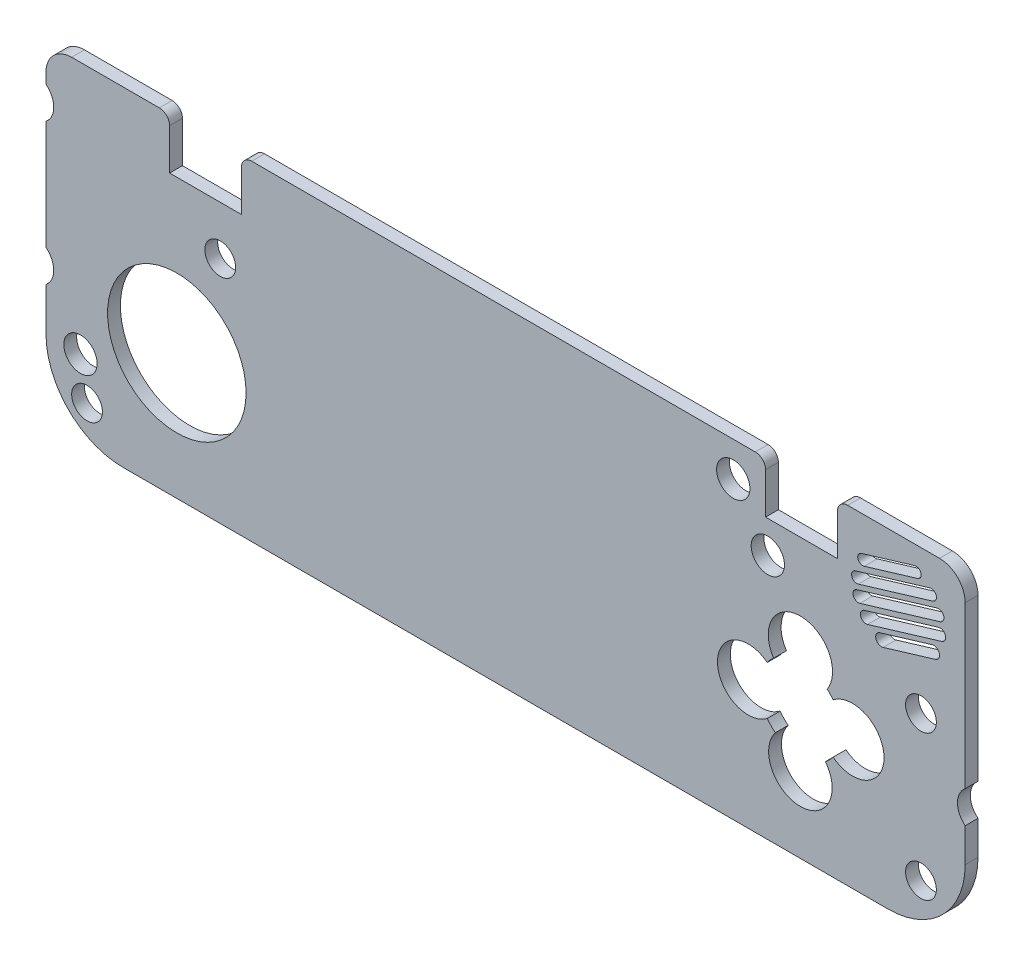
SolidWorks part; units mm, degrees
ref_plane "Plan de face" through (0, 0, 0) normal (0, 0, 1) x (1, 0, 0)
ref_plane "Plan de dessus" through (0, 0, 0) normal (0, 1, 0) x (1, 0, 0)
ref_plane "Plan de droite" through (0, 0, 0) normal (1, 0, 0) x (0, 0, -1)
sketch "Esquisse1" plane through (0, 0, 0) normal (0, 0, 1) x (1, 0, 0)
  line L1 (-89.2039, 33.3448) -> (79.9661, 33.3448)
  line L2 (-94.2039, 28.3448) -> (-94.2039, -15.8852)
  line L3 (-79.2039, -30.8852) -> (69.9661, -30.8852)
  line L4 (84.9661, 28.3448) -> (84.9661, -15.8852)
  arc A0 (-89.2039, 33.3448) -> (-94.2039, 28.3448) centre (-89.2039, 28.3448) ccw
  arc A1 (79.9661, 33.3448) -> (84.9661, 28.3448) centre (79.9661, 28.3448) cw
  arc A2 (69.9661, -30.8852) -> (84.9661, -15.8852) centre (69.9661, -15.8852) ccw
  arc A3 (-94.2039, -15.8852) -> (-79.2039, -30.8852) centre (-79.2039, -15.8852) ccw
  point P6 (-94.2039, 33.3448)
  point P9 (84.9661, 33.3448)
  point P12 (84.9661, -30.8852)
  dimension "D3" = 5
  dimension "D4" = 5
  dimension "D5" = 15
  dimension "D6" = 15
  dimension "D1" = 179.17
  dimension "D2" = 64.23
extrude "Boss.-Extru.1" add sketch "Esquisse1" along normal blind 2.5 contours L1 A1 L4 A2 L3 A3 L2 A0
sketch "12x12 Button" plane through (0, 0, 2.5) normal (0, 0, 1) x (1, 0, 0)
  line L0 (84.9661, 28.3448) -> (84.9661, -15.8852) construction
  line L1 (-79.2039, -30.8852) -> (69.9661, -30.8852) construction
  line L2 (52.8461, 3.7748) -> (52.8461, -15.9152)
  line L3 (42.6861, -5.7552) -> (63.0061, -5.7552)
  circle A0 centre (42.6861, -5.7552) radius 5.9988
  circle A1 centre (52.8461, 3.7748) radius 6.2634
  circle A2 centre (52.8461, -15.9152) radius 6.1927
  circle A3 centre (63.0061, -5.7552) radius 6.14
  arc A5 (46.3825, -1.0306) -> (47.6252, 0.3146) centre (52.8461, -5.7552) cw
  arc A6 (59.2204, -0.9212) -> (58.0635, 0.3093) centre (52.8461, -5.7552) ccw
  arc A7 (46.3874, -10.476) -> (47.9701, -12.0975) centre (52.8461, -5.7552) ccw
  arc A10 (57.722, -12.0975) -> (59.2204, -10.5893) centre (52.8461, -5.7552) ccw
  dimension "D1" = 21.96
  dimension "D2" = 32.12
  dimension "D3" = 42.28
  dimension "D4" = 32.12
  dimension "D5" = 14.97
  dimension "D6" = 34.66
  dimension "D7" = 25.13
  dimension "D8" = 25.13
extrude "Enlèv. mat.-Extru.14" cut sketch "12x12 Button" against normal blind 10
sketch "Joystick" plane through (0, 0, 2.5) normal (0, 0, 1) x (1, 0, 0)
  line L0 (-79.2039, -30.8852) -> (69.9661, -30.8852) construction
  line L1 (-94.2039, 28.3448) -> (-94.2039, -15.8852) construction
  circle A0 centre (-68.7039, -6.3252) radius 13.5
  dimension "D1" = 24.56
  dimension "D2" = 25.5
extrude "Enlèv. mat.-Extru.2" cut sketch "Joystick" against normal blind 2.5
sketch "Esquisse2" plane through (0, 0, 2.5) normal (0, 0, 1) x (1, 0, 0)
  line L0 (-89.2039, 33.3448) -> (79.9661, 33.3448) construction
  line L1 (46.0561, 33.3448) -> (60.0561, 33.3448)
  line L2 (46.0561, 33.3448) -> (46.0561, 23.3448)
  line L3 (46.0561, 23.3448) -> (60.0561, 23.3448)
  line L4 (60.0561, 33.3448) -> (60.0561, 23.3448)
  line L5 (84.9661, 28.3448) -> (84.9661, -15.8852) construction
  dimension "D1" = 24.91
  dimension "D2" = 14
extrude "Enlèv. mat.-Extru.3" cut sketch "Esquisse2" against normal blind 10
fillet "Congé1" radius 2 1 edges at (46.0561, 33.3448, 1.25)
fillet "Congé2" radius 2 1 edges at (60.0561, 33.3448, 1.25)
sketch "Esquisse3" plane through (0, 0, 2.5) normal (0, 0, 1) x (1, 0, 0)
  line L0 (-89.2039, 33.3448) -> (44.0561, 33.3448) construction
  line L1 (-70.1039, 33.3448) -> (-56.1039, 33.3448)
  line L2 (-70.1039, 33.3448) -> (-70.1039, 23.3448)
  line L3 (-70.1039, 23.3448) -> (-56.1039, 23.3448)
  line L4 (-56.1039, 33.3448) -> (-56.1039, 23.3448)
  line L5 (-94.2039, 28.3448) -> (-94.2039, -15.8852) construction
  dimension "D1" = 24.1
  dimension "D2" = 10
  dimension "D3" = 14
extrude "Enlèv. mat.-Extru.4" cut sketch "Esquisse3" against normal blind 10 contours L2 L1 L4 L3
fillet "Congé3" radius 2 1 edges at (-70.1039, 33.3448, 1.25)
fillet "Congé4" radius 2 1 edges at (-56.1039, 33.3448, 1.25)
sketch "Esquisse4" plane through (0, 0, 2.5) normal (0, 0, 1) x (1, 0, 0)
  line L0 (84.9661, 28.3448) -> (84.9661, -15.8852) construction
  line L1 (64.1511, 18.9874) -> (79.781, 23.7022) construction
  line L2 (62.0561, 33.3448) -> (79.9661, 33.3448) construction
  line L3 (63.8482, 19.9918) -> (79.478, 24.7066)
  line L4 (64.4541, 17.983) -> (80.084, 22.6978)
  line L5 (63.8337, 22.048) -> (78.3531, 26.4278) construction
  line L6 (63.5398, 23.0223) -> (78.0592, 27.4021)
  line L7 (64.1276, 21.0736) -> (78.647, 25.4535)
  line L8 (65.0061, 25.6097) -> (75.4066, 28.7471) construction
  line L9 (64.7213, 26.554) -> (75.1217, 29.6914)
  line L10 (65.291, 24.6654) -> (75.6914, 27.8027)
  line L11 (65.627, 16.2022) -> (80.0915, 20.5654) construction
  line L12 (65.3147, 17.2374) -> (79.7793, 21.6007)
  line L13 (65.9393, 15.1669) -> (80.4038, 19.5302)
  line L14 (68.6474, 13.8871) -> (78.8552, 16.9663) construction
  line L15 (68.3228, 14.9633) -> (78.5305, 18.0425)
  line L16 (68.9721, 12.8109) -> (79.1798, 15.8901)
  circle A0 centre (71.9661, 21.3448) radius 10
  circle A1 centre (71.9661, 21.3448) radius 8.1628
  arc A2 (63.8482, 19.9918) -> (64.4541, 17.983) centre (64.1511, 18.9874) ccw
  arc A3 (80.084, 22.6978) -> (79.478, 24.7066) centre (79.781, 23.7022) ccw
  arc A4 (63.5398, 23.0223) -> (64.1276, 21.0736) centre (63.8337, 22.048) ccw
  arc A5 (78.647, 25.4535) -> (78.0592, 27.4021) centre (78.3531, 26.4278) ccw
  arc A6 (64.7213, 26.554) -> (65.291, 24.6654) centre (65.0061, 25.6097) ccw
  arc A7 (75.6914, 27.8027) -> (75.1217, 29.6914) centre (75.4066, 28.7471) ccw
  arc A8 (65.3147, 17.2374) -> (65.9393, 15.1669) centre (65.627, 16.2022) ccw
  arc A9 (80.4038, 19.5302) -> (79.7793, 21.6007) centre (80.0915, 20.5654) ccw
  arc A10 (68.3228, 14.9633) -> (68.9721, 12.8109) centre (68.6474, 13.8871) ccw
  arc A11 (79.1798, 15.8901) -> (78.5305, 18.0425) centre (78.8552, 16.9663) ccw
  point P9 (71.9661, 21.3448)
  point P16 (71.0934, 24.2379)
  point P25 (70.2064, 27.1784)
  point P36 (72.8593, 18.3838)
  point P47 (73.7513, 15.4267)
  dimension "D1" = 13
  dimension "D2" = 12
  dimension "D4" = 0
  dimension "D5" = 1.0673
  dimension "D6" = 360
  dimension "D7" = 360
  dimension "D8" = 0.8833
extrude "Enlèv. mat.-Extru.8" cut sketch "Esquisse4" against normal blind 10 contours L4 A1 L3 | L3 A2 A0 L4 A1 | L6 A4 A0 A1 | L9 A6 A0 A1 | L10 A7 A1 L9 A6 | A1 A9 L12 A8 L13 | A1 A8 A0 L13 | A1 A10 A0 L16 | A1 A11 L15 A10 L16 | L16 A11 A0 A1 | A0 A9 A1 L13 | A0 A3 L3 A1 L4 | A0 A5 L6 A1 | L7 A5 A1 L6 A4 | A0 A7 L9 A1
sketch "Esquisse5" plane through (0, 0, 2.5) normal (0, 0, 1) x (1, 0, 0)
  line L0 (84.9661, 28.3448) -> (84.9661, -15.8852) construction
  line L1 (-79.2039, -30.8852) -> (69.9661, -30.8852) construction
  line L2 (-94.2039, 28.3448) -> (-94.2039, -15.8852) construction
  line L7 (62.0561, 33.3448) -> (79.9661, 33.3448) construction
  line L8 (-54.1039, 33.3448) -> (44.0561, 33.3448) construction
  circle A0 centre (76.3461, -22.8852) radius 3
  circle A1 centre (-86.2039, -23.5352) radius 3
  circle A2 centre (76.3461, 5.3448) radius 3
  circle A3 centre (-60.2339, 13.8348) radius 3
  circle A4 centre (-87.4839, -15.9152) radius 3.25
  circle A5 centre (39.7561, 26.6248) radius 3.25
  circle A6 centre (46.4961, 17.1048) radius 3.25
  dimension "D1" = 8.62
  dimension "D3" = 7.35
  dimension "D5" = 8.62
  dimension "D7" = 19.51
  dimension "D9" = 6.72
  dimension "D11" = 6.72
  dimension "D13" = 38.47
  dimension "D2" = 8
  dimension "D4" = 8
  dimension "D6" = 28
  dimension "D8" = 33.97
  dimension "D10" = 14.97
  dimension "D12" = 45.21
  dimension "D14" = 16.24
extrude "Enlèv. mat.-Extru.9" cut sketch "Esquisse5" against normal blind 10
sketch "Esquisse6" plane through (0, 0, 2.5) normal (0, 0, 1) x (1, 0, 0)
  line L0 (-76.1808, -30.8852) -> (-76.1808, -4.3852)
  line L1 (-79.2039, -30.8852) -> (69.9661, -30.8852) construction
  line L2 (-76.1808, -4.3852) -> (-94.2039, -4.3852)
  line L3 (-94.2039, 28.3448) -> (-94.2039, -15.8852) construction
  line L4 (-94.2039, -4.3852) -> (-99.2039, -4.3852)
  line L5 (-80.6539, 33.3448) -> (-80.6539, 23.1548)
  line L6 (-89.2039, 33.3448) -> (-72.1039, 33.3448) construction
  line L7 (-80.6539, 23.1548) -> (-94.2039, 23.1548)
  line L8 (-94.2039, 23.1548) -> (-99.2039, 23.1548)
  line L9 (68.4263, -30.8852) -> (68.4263, -6.1652)
  line L10 (68.4263, -6.1652) -> (84.9661, -6.1652)
  line L11 (84.9661, 28.3448) -> (84.9661, -15.8852) construction
  line L12 (84.9661, -6.1652) -> (89.9661, -6.1652)
  circle A0 centre (-96.7039, -4.3852) radius 4
  circle A1 centre (-96.7039, 23.1548) radius 4
  circle A2 centre (87.4661, -6.1652) radius 4
extrude "Enlèv. mat.-Extru.15" cut sketch "Esquisse6" against normal blind 10
